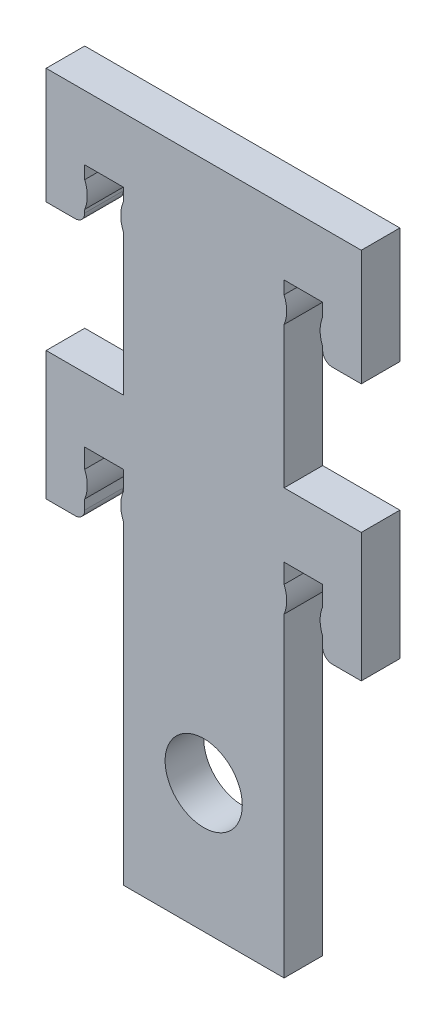
SolidWorks part; units mm, degrees
ref_plane "Front Plane" through (0, 0, 0) normal (0, 0, 1) x (1, 0, 0)
ref_plane "Top Plane" through (0, 0, 0) normal (0, 1, 0) x (1, 0, 0)
ref_plane "Right Plane" through (0, 0, 0) normal (1, 0, 0) x (0, 0, -1)
sketch "Sketch1" plane through (0, 0, 0) normal (0, 0, 1) x (1, 0, 0)
  line L0 (6, 12.7553) -> (-18.5, 12.7553)
  line L1 (6, 12.7553) -> (6, 3.7553)
  line L2 (6, 3.7553) -> (3, 3.7553)
  line L3 (3, 3.7553) -> (3, 4.7553)
  line L4 (3, 7.7553) -> (0, 7.7553)
  line L5 (0, 7.7553) -> (0, 6.7553)
  line L6 (0, -6.2447) -> (6, -6.2447)
  line L7 (6, -16.2447) -> (6, -6.2447)
  line L8 (6, -16.2447) -> (3, -16.2447)
  line L9 (0, -11.2447) -> (0, -12.7447)
  line L10 (3, -11.2447) -> (0, -11.2447)
  line L11 (3, 6.7553) -> (3, 7.7553)
  line L12 (0, -39.2447) -> (-12.5, -39.2447)
  line L13 (-6.25, 19.1088) -> (-6.25, 4.2553) construction
  line L14 (-12.5, -11.2447) -> (-12.5, -12.7447)
  line L15 (-15.5, -11.2447) -> (-12.5, -11.2447)
  line L16 (-15.5, -16.2447) -> (-15.5, -14.7447)
  line L17 (-18.5, -16.2447) -> (-15.5, -16.2447)
  line L18 (-18.5, -6.2447) -> (-18.5, -16.2447)
  line L19 (-12.5, -6.2447) -> (-18.5, -6.2447)
  line L20 (-12.5, 7.7553) -> (-12.5, 6.7553)
  line L21 (-15.5, 7.7553) -> (-12.5, 7.7553)
  line L22 (-15.5, 3.7553) -> (-15.5, 4.7553)
  line L23 (-18.5, 3.7553) -> (-15.5, 3.7553)
  line L24 (-18.5, 12.7553) -> (-18.5, 3.7553)
  line L25 (3, -14.7447) -> (3, -16.2447)
  line L26 (0, 4.7553) -> (0, -6.2447)
  line L27 (3, -11.2447) -> (3, -12.7447)
  line L28 (-15.5, -12.7447) -> (-15.5, -11.2447)
  line L29 (1.5, 7.7553) -> (1.5, 9.9531) construction
  line L30 (-12.5, 4.7553) -> (-12.5, -6.2447)
  line L31 (-15.5, 6.7553) -> (-15.5, 7.7553)
  line L32 (-12.5, -14.7447) -> (-12.5, -39.2447)
  line L33 (0, -14.7447) -> (0, -39.2447)
  circle A0 centre (-6.25, -29.2447) radius 3
  arc A1 (3, 4.7553) -> (3, 6.7553) centre (5.4, 5.7553) cw
  arc A2 (0, 4.7553) -> (0, 6.7553) centre (-2.4, 5.7553) ccw
  arc A3 (3, -14.7447) -> (3, -12.7447) centre (5.4, -13.7447) cw
  arc A4 (0, -14.7447) -> (0, -12.7447) centre (-2.4, -13.7447) ccw
  arc A5 (-15.5, -14.7447) -> (-15.5, -12.7447) centre (-17.9, -13.7447) ccw
  arc A6 (-12.5, -14.7447) -> (-12.5, -12.7447) centre (-10.1, -13.7447) cw
  arc A7 (-15.5, 4.7553) -> (-15.5, 6.7553) centre (-17.9, 5.7553) ccw
  arc A8 (-12.5, 4.7553) -> (-12.5, 6.7553) centre (-10.1, 5.7553) cw
  point P18 (-6.25, -39.2447)
  point P29 (-6.25, 12.7553)
  dimension "D14" = 6
  dimension "D15" = 10
  dimension "D1" = 9
  dimension "D2" = 3
  dimension "D3" = 4
  dimension "D4" = 3
  dimension "D5" = 14
  dimension "D6" = 6
  dimension "D7" = 10
  dimension "D8" = 5
  dimension "D9" = 3
  dimension "D11" = 28
  dimension "D12" = 6.25
  dimension "D13" = 12.25
extrude "Boss-Extrude1" add sketch "Sketch1" along normal blind 3
fillet "Fillet3" radius 0.75 1 edges at (3, 3.7553, 1.5)
fillet "Fillet4" radius 0.75 3 edges at (3, -16.2447, 1.5) (-15.5, -16.2447, 1.5) (-15.5, 3.7553, 1.5)
